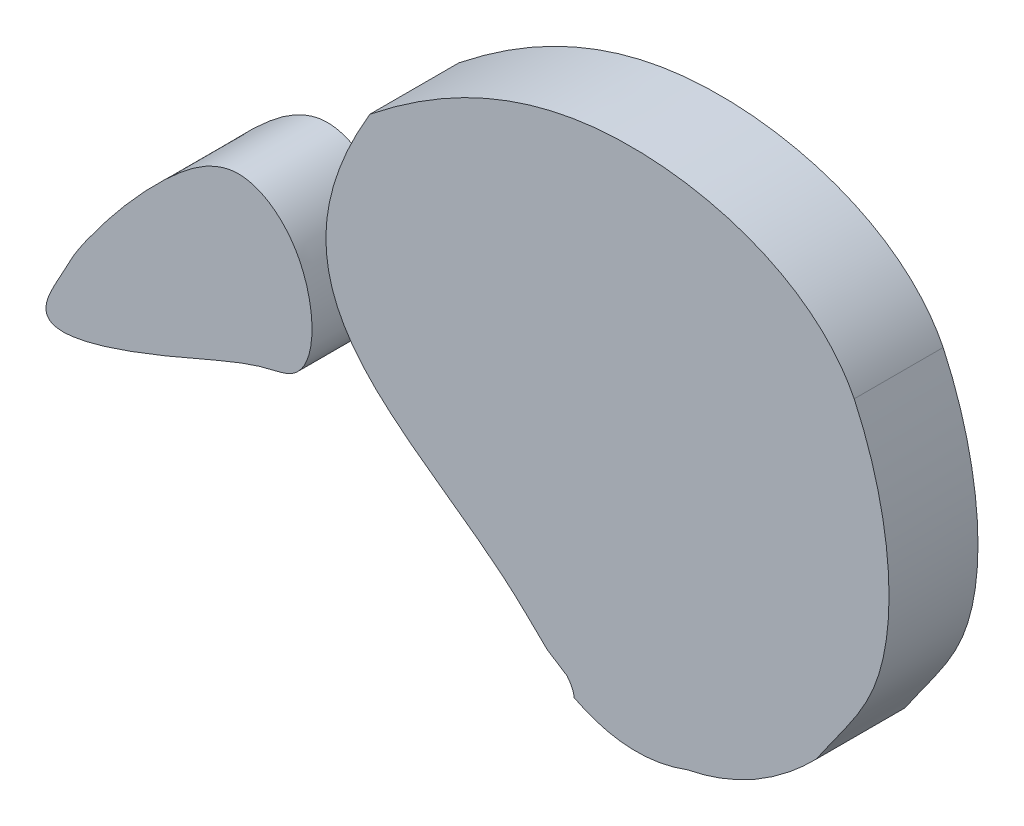
SolidWorks part; units mm, degrees
ref_plane "Front Plane" through (0, 0, 0) normal (0, 0, 1) x (1, 0, 0)
ref_plane "Top Plane" through (0, 0, 0) normal (0, 1, 0) x (1, 0, 0)
ref_plane "Right Plane" through (0, 0, 0) normal (1, 0, 0) x (0, 0, -1)
sketch "Sketch1" plane through (0, 0, 0) normal (0, 0, 1) x (1, 0, 0)
  spline S0 degree 3 poles (-78.5124, -40.0771) (-58.6161, -14.5843) (-47.9219, 15.2113) (23.9242, 21.2622) (12.6396, 1.4175) knots 0 0 0 0 0.637666 1 1 1 1
  spline S1 degree 3 poles (-31.5509, 22.6875) (-29.7334, 27.381) (-20.9532, 38.7162) (-11.8905, 45.2867) (-3.1002, 39.2694) (-2.7893, 27.4294) (-9.7403, 26.532) (-38.7108, 13.4204) (-31.5509, 22.6875) (-29.7334, 27.381) (-20.9532, 38.7162) knots -0.609626 -0.556636 -0.110252 0 0.120348 0.195891 0.256652 0.359848 0.390374 0.443364 0.889748 1 1.120348 1.195891 1.256652 only from (-28.3902, 28.8973) to (-28.3902, 28.8973)
  spline S2 degree 2 poles (38.6106, 71.1635) (39.2609, 70.9981) (39.6095, 70.8961) knots 0.963854 0.963854 0.963854 1 1 1
  spline S3 degree 3 poles (2.7816, 56.4779) (9.7551, 62.0195) (27.3967, 71.9933) (52.4442, 64.8942) (56.5463, 55.1277) knots 0 0 0 0 0.462605 1 1 1 1
  spline S4 degree 2 poles (-81.2929, -28.1439) (-83.196, -36.6495) (-78.5124, -40.0771) knots 0 0 0 0.81794 0.81794 0.81794
  spline S5 degree 3 poles (-81.2929, -36.2783) (-67.8472, -12.0192) (-36.8818, 18.8325) (6.054, 26.1159) (24.5041, 13.76) knots 0 0 0 0 0.593505 0.977243 0.977243 0.977243 0.977243
  spline S6 degree 3 poles (24.5041, 13.76) (24.9644, 13.2246) (26.267, 10.2702) (20.9376, 4.4845) (14.5874, 1.682) (12.6396, 1.4175) knots 0.123396 0.123396 0.123396 0.123396 0.21858 0.613348 0.919481 0.919481 0.919481 0.919481
  spline S8 degree 2 poles (37.8211, 11.4277) (45.4854, 12.9578) (51.9461, 19.5147) knots 0.435157 0.435157 0.435157 1 1 1
  spline S9 degree 3 poles (39.6095, 70.8961) (47.0124, 68.3178) (58.3753, 58.4182) (62.3747, 32.3529) (54.3258, 23.0431) (51.9461, 19.5147) knots 0.005203 0.005203 0.005203 0.005203 0.309691 0.684335 0.84012 0.84012 0.84012 0.84012
  spline S10 degree 3 poles (38.6106, 71.1635) (31.4384, 72.7032) (11.3656, 71.4785) (-20.3275, 46.7055) (-39.7926, 20.0589) (-61.5719, -2.42) (-81.2929, -28.1439) knots 0.003532 0.003532 0.003532 0.003532 0.126811 0.380842 0.641525 1 1 1 1
  spline S11 degree 3 poles (2.7816, 56.4779) (-10.9182, 33.3523) (9.3737, 28.4413) (21.2759, 16.1363) (22.3296, 15.151) knots 0 0 0 0 0.747546 0.818239 0.818239 0.818239 0.818239
  spline S12 degree 3 poles (-93.363, -35.2314) (-54.4397, 11.1942) (-35.3618, 65.7981) (34.0917, 80.9531) (76.164, 63.4686) (64.4385, 10.8332) (21.4178, -12.8994) (-8.3402, 12.187) (-35.1383, -11.4181) (-56.2436, -26.9249) (-72.1926, -56.5848) (-93.363, -35.2314) (-54.4397, 11.1942) (-35.3618, 65.7981) knots -0.110155 -0.04935 -0.004935 0 0.306256 0.397794 0.474693 0.577423 0.7001 0.736101 0.823546 0.889845 0.95065 0.995065 1 1.306256 1.397794 1.474693 only from (-87.426, -28.1439) to (-87.426, -28.1439)
  spline S13 degree 2 poles (37.8211, 11.4277) (31.2984, 8.9743) (25.2976, 12.0538) knots 0 0 0 1 1 1
  dimension "D1" = 32.5864
extrude "Boss-Extrude1" add sketch "Sketch1" along normal blind 9.8
